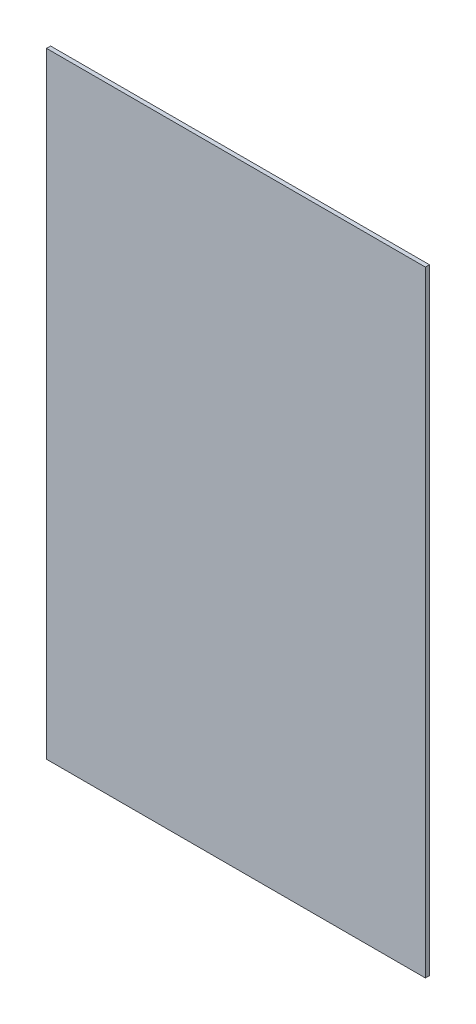
SolidWorks part; units mm, degrees
ref_plane "Front Plane" through (0, 0, 0) normal (0, 0, 1) x (1, 0, 0)
ref_plane "Top Plane" through (0, 0, 0) normal (0, 1, 0) x (1, 0, 0)
ref_plane "Right Plane" through (0, 0, 0) normal (1, 0, 0) x (0, 0, -1)
sketch "Sketch1" plane through (0, 0, 0) normal (0, 0, 1) x (1, 0, 0)
  line L1 (-2921.2324, -1400.4476) -> (-1161.2324, -1400.4476)
  line L2 (-2921.2324, -1400.4476) -> (-2921.2324, 1459.5524)
  line L3 (-2921.2324, 1459.5524) -> (-1161.2324, 1459.5524)
  line L4 (-1161.2324, -1400.4476) -> (-1161.2324, 1459.5524)
extrude "Boss-Extrude1" add sketch "Sketch1" along normal blind 19
